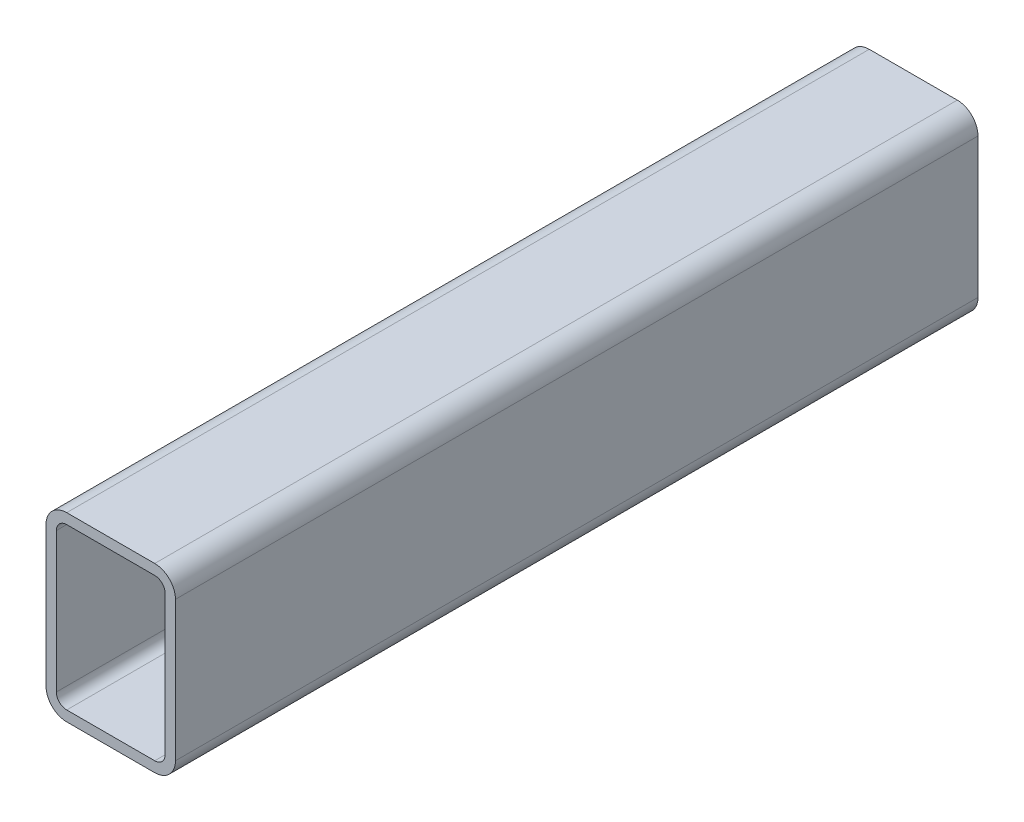
SolidWorks part; units mm, degrees
material "Q235"
ref_plane "前视基准面" through (0, 0, 0) normal (0, 0, 1) x (1, 0, 0)
ref_plane "上视基准面" through (0, 0, 0) normal (0, 1, 0) x (1, 0, 0)
ref_plane "右视基准面" through (0, 0, 0) normal (1, 0, 0) x (0, 0, -1)
sketch "尺寸草图" plane through (0, 0, 0) normal (0, 0, 1) x (1, 0, 0)
  line L0 (-25.8313, 0) -> (21, 0) construction
  line L1 (0, 56.0755) -> (0, -63.3818) construction
  line L2 (-17, 31) -> (17, 31)
  line L3 (-17, 35) -> (17, 35)
  line L4 (-25, 27) -> (-25, -27)
  line L5 (-17, -35) -> (17, -35)
  line L6 (25, 27) -> (25, -27)
  line L7 (21, 27) -> (21, -27)
  line L8 (-17, -31) -> (17, -31)
  line L9 (-21, 27) -> (-21, -27)
  line L10 (-25, 35) -> (-25, -35) construction
  line L11 (-25, -35) -> (25, -35) construction
  line L12 (-21, -31) -> (21, -31) construction
  line L13 (-21, 31) -> (-21, -31) construction
  line L14 (21, 31) -> (21, -31) construction
  line L15 (25, 35) -> (25, -35) construction
  line L16 (-21, 31) -> (21, 31) construction
  line L17 (-25, 35) -> (25, 35) construction
  arc A0 (-25, -27) -> (-17, -35) centre (-17, -27) ccw
  arc A1 (-17, -31) -> (-21, -27) centre (-17, -27) cw
  arc A2 (21, -27) -> (17, -31) centre (17, -27) cw
  arc A3 (17, -35) -> (25, -27) centre (17, -27) ccw
  arc A4 (17, 31) -> (21, 27) centre (17, 27) cw
  arc A5 (17, 35) -> (25, 27) centre (17, 27) cw
  arc A6 (-17, 31) -> (-21, 27) centre (-17, 27) ccw
  arc A7 (-17, 35) -> (-25, 27) centre (-17, 27) ccw
  dimension "D2" = 8
  dimension "H" = 70
  dimension "B" = 50
  dimension "t" = 4
extrude "凸台-拉伸1" add sketch "尺寸草图" along normal mid plane 310
